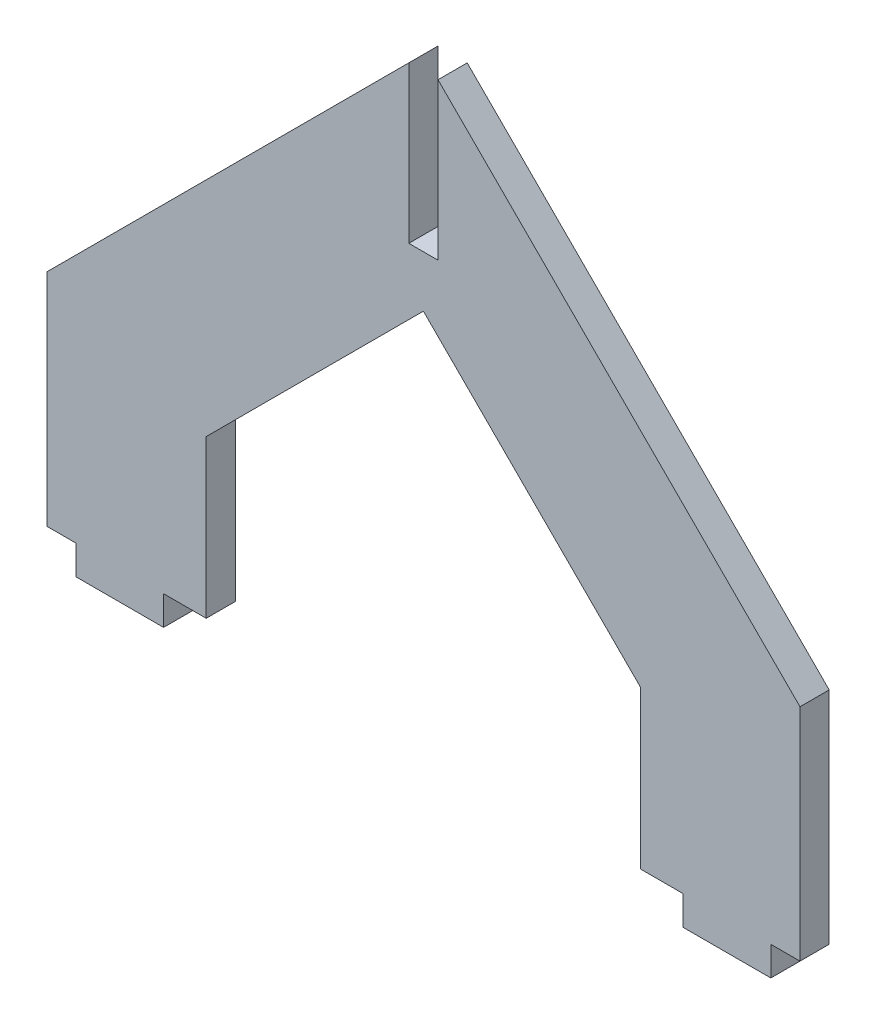
SolidWorks part; units mm, degrees
ref_plane "Front Plane" through (0, 0, 0) normal (0, 0, 1) x (1, 0, 0)
ref_plane "Top Plane" through (0, 0, 0) normal (0, 1, 0) x (1, 0, 0)
ref_plane "Right Plane" through (0, 0, 0) normal (1, 0, 0) x (0, 0, -1)
sketch "Sketch1" plane through (0, 0, 0) normal (0, 0, 1) x (1, 0, 0)
  line L3 (34.6519, 42.7239) -> (99.139, 107.211)
  line L4 (99.139, 107.211) -> (200, 6.35)
  line L5 (200, 6.35) -> (185, 6.35)
  line L6 (185, 6.35) -> (185, 0)
  line L7 (185, 0) -> (170, 0)
  line L8 (170, 0) -> (170, 6.35)
  line L9 (170, 6.35) -> (165, 6.35)
  line L10 (165, 6.35) -> (100.675, 70.675)
  line L11 (100.675, 70.675) -> (61.9504, 31.9504)
  line L14 (61.9504, 31.9504) -> (61.9504, 5)
  line L15 (61.9504, 5) -> (54.6519, 5)
  line L16 (54.6519, 5) -> (54.6519, 0)
  line L17 (54.6519, 0) -> (39.6519, 0)
  line L18 (39.6519, 0) -> (39.6519, 5)
  line L19 (39.6519, 5) -> (34.6519, 5)
  line L20 (34.6519, 5) -> (34.6519, 42.7239)
  point P0 (37.1519, 5)
  dimension "D1" = 5
  dimension "D2" = 5
  dimension "D3" = 5
  dimension "D4" = 15
extrude "Boss-Extrude1" add sketch "Sketch1" along normal blind 5
sketch "Sketch2" plane through (0, 0, 5) normal (0, 0, 1) x (1, 0, 0)
  line L0 (96.639, 104.711) -> (96.639, 80.711)
  line L1 (99.139, 107.211) -> (34.6519, 42.7239) construction
  line L2 (96.639, 80.711) -> (101.639, 80.711)
  line L3 (101.639, 80.711) -> (101.639, 104.711)
  line L4 (200, 6.35) -> (99.139, 107.211) construction
  line L5 (101.639, 104.711) -> (99.139, 107.211)
  line L6 (99.139, 107.211) -> (96.639, 104.711)
  line L7 (99.139, 106.35) -> (99.139, 50106.35) construction
  dimension "D1" = 5
  dimension "D2" = 24
extrude "Cut-Extrude1" cut sketch "Sketch2" against normal blind 10
sketch "Sketch3" plane through (0, 0, 5) normal (0, 0, 1) x (1, 0, 0)
  line L0 (99.139, -919.289) -> (99.139, 49080.711) construction
  line L1 (96.639, 80.711) -> (101.639, 80.711) construction
  line L3 (99.139, 109.0222) -> (201.1551, 109.0222)
  line L4 (99.139, 109.0222) -> (99.139, -5.3414)
  line L5 (99.139, -5.3414) -> (201.1551, -5.3414)
  line L6 (201.1551, 109.0222) -> (201.1551, -5.3414)
  point P5 (99.139, 80.711)
extrude "Cut-Extrude2" cut sketch "Sketch3" against normal blind 10
mirror "Mirror1" about plane through (99.139, 109.0222, -5) normal (-1, 0, 0) of "Boss-Extrude1"
sketch "Sketch4" plane through (0, 0, 0) normal (0, 0, -1) x (-1, 0, 0)
  line L0 (-34.6519, 5) -> (-34.6519, 50005) construction
  line L2 (-34.6519, 73.1172) -> (7.4443, 73.1172)
  line L3 (-34.6519, 73.1172) -> (-34.6519, -7.6442)
  line L4 (-34.6519, -7.6442) -> (7.4443, -7.6442)
  line L5 (7.4443, 73.1172) -> (7.4443, -7.6442)
extrude "Cut-Extrude3" cut sketch "Sketch4" against normal blind 10
sketch "Sketch5" plane through (0, 0, 0) normal (0, 0, -1) x (-1, 0, 0)
  line L1 (-101.639, 136.4717) -> (-96.639, 136.4717)
  line L2 (-101.639, 136.4717) -> (-101.639, 77.9503)
  line L3 (-101.639, 77.9503) -> (-96.639, 77.9503)
  line L4 (-96.639, 136.4717) -> (-96.639, 77.9503)
  line L5 (-101.639, 136.4717) -> (-96.639, 77.9503) construction
  line L6 (-101.639, 77.9503) -> (-96.639, 136.4717) construction
  point P0 (-99.139, 107.211)
  dimension "D1" = 5
extrude "Cut-Extrude4" cut sketch "Sketch5" against normal blind 10
